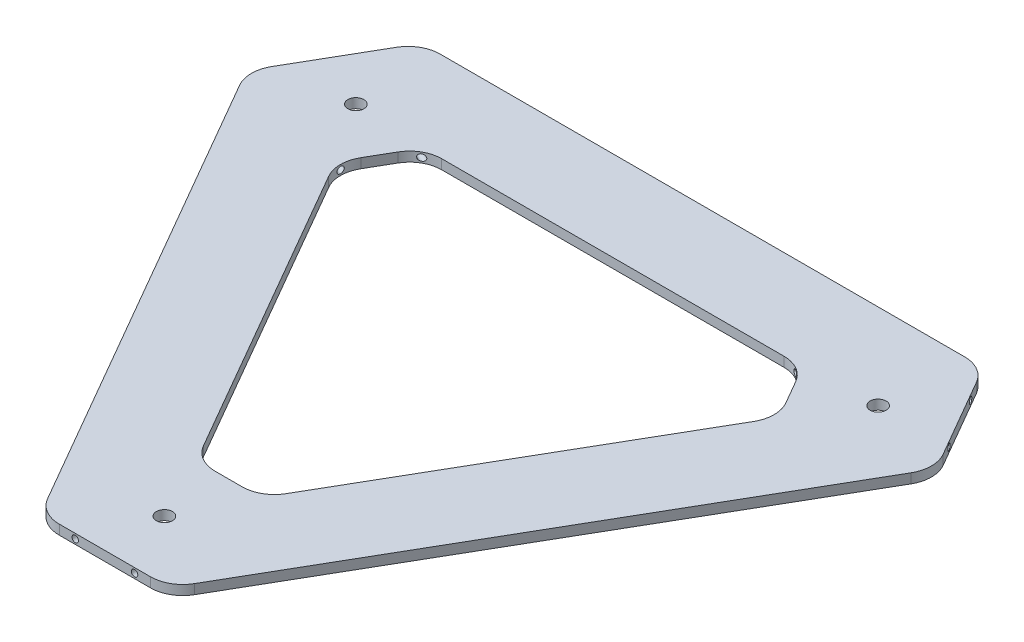
SolidWorks part; units mm, degrees
ref_plane "Front Plane" through (0, 0, 0) normal (0, 0, 1) x (1, 0, 0)
ref_plane "Top Plane" through (0, 0, 0) normal (0, 1, 0) x (1, 0, 0)
ref_plane "Right Plane" through (0, 0, 0) normal (1, 0, 0) x (0, 0, -1)
sketch "Sketch1" plane through (0, 0, 0) normal (0, 1, 0) x (1, 0, 0)
  line L0 (-132.8622, 80.6266) -> (-114.8184, 111.8764)
  line L1 (114.7578, 111.8982) -> (132.8579, 80.6002)
  line L2 (-103.821, 118.2259) -> (103.763, 118.2403)
  line L3 (-18.0944, -118.2403) -> (18.0401, -118.2403)
  line L4 (-132.8638, 67.9283) -> (-29.0942, -111.8881)
  line L5 (132.8618, 67.891) -> (29.038, -111.8915)
  line L6 (-84.0133, 67.0223) -> (-78.6427, 76.3234)
  line L7 (84.1416, 67.0751) -> (78.7703, 76.363)
  line L8 (-84.0158, 54.3257) -> (-16.3805, -62.9162)
  line L9 (-5.3798, -69.27) -> (5.3567, -69.27)
  line L10 (16.3521, -62.9253) -> (84.1432, 54.3618)
  line L11 (67.7734, 82.705) -> (-67.6475, 82.673)
  arc A0 (18.0401, -118.2403) -> (29.038, -111.8915) centre (18.0401, -105.5403) ccw
  arc A1 (-29.0942, -111.8881) -> (-18.0944, -118.2403) centre (-18.0944, -105.5403) ccw
  arc A2 (132.8618, 67.891) -> (132.8579, 80.6002) centre (121.864, 74.2422) ccw
  arc A3 (114.7578, 111.8982) -> (103.763, 118.2403) centre (103.7639, 105.5403) ccw
  arc A4 (-103.821, 118.2259) -> (-114.8184, 111.8764) centre (-103.8201, 105.5259) ccw
  arc A5 (-132.8622, 80.6266) -> (-132.8638, 67.9283) centre (-121.864, 74.2761) ccw
  arc A6 (-16.3805, -62.9162) -> (-5.3798, -69.27) centre (-5.3798, -56.57) ccw
  arc A7 (5.3567, -69.27) -> (16.3521, -62.9253) centre (5.3567, -56.57) ccw
  arc A8 (84.1432, 54.3618) -> (84.1416, 67.0751) centre (73.1477, 60.7171) ccw
  arc A9 (78.7703, 76.363) -> (67.7734, 82.705) centre (67.7764, 70.005) ccw
  arc A10 (-67.6475, 82.673) -> (-78.6427, 76.3234) centre (-67.6445, 69.973) ccw
  arc A11 (-84.0133, 67.0223) -> (-84.0158, 54.3257) centre (-73.015, 60.6719) ccw
  circle A12 centre (-103.3309, 84.381) radius 3.175
  circle A13 centre (-0.0284, -94.7026) radius 3.175
  circle A14 centre (103.3369, 84.3971) radius 3.175
  dimension "D1" = 6.35
  dimension "D2" = 12.7
  dimension "D4" = 5.3567
  dimension "D5" = 16.3521
  dimension "D6" = 18.0401
  dimension "D7" = 29.038
  dimension "D8" = 67.7734
  dimension "D9" = 67.7764
  dimension "D10" = 73.1477
  dimension "D11" = 78.7703
  dimension "D12" = 103.763
  dimension "D13" = 103.3369
  dimension "D14" = 103.7639
  dimension "D15" = 114.7578
  dimension "D16" = 121.864
  dimension "D17" = 5.3798
  dimension "D18" = 16.3805
  dimension "D19" = 18.0944
  dimension "D20" = 0.0284
  dimension "D21" = 29.0942
  dimension "D22" = 67.6445
  dimension "D23" = 73.015
  dimension "D24" = 103.8201
  dimension "D25" = 114.8184
  dimension "D26" = 54.3257
  dimension "D27" = 67.891
  dimension "D31" = 103.3309
  dimension "D45" = 84.381
  dimension "D46" = 84.3971
  dimension "D57" = 94.7026
extrude "Boss-Extrude1" add sketch "Sketch1" along normal blind 3.81
sketch "Sketch2" plane through (0, 0, 0) normal (0, 1, 0) x (1, 0, 0)
  line L0 (-80.979, -21.9799) -> (123.8078, 96.2492) construction
  line L1 (-132.8638, 67.9283) -> (-29.0942, -111.8881) construction
  line L2 (114.7578, 111.8982) -> (132.8579, 80.6002) construction
  line L3 (-0.029, 118.2331) -> (-0.0271, -118.2403) construction
  line L4 (-103.821, 118.2259) -> (103.763, 118.2403) construction
  line L5 (-18.0944, -118.2403) -> (18.0401, -118.2403) construction
  line L6 (80.9499, -22.0002) -> (-123.8403, 96.2515) construction
  line L7 (132.8618, 67.891) -> (29.038, -111.8915) construction
  line L8 (-132.8622, 80.6266) -> (-114.8184, 111.8764) construction
  line L9 (-129.7133, 86.0802) -> (-136.3122, 89.8906) construction
  line L10 (-117.967, 106.4226) -> (-124.5659, 110.233) construction
  line L11 (-117.967, 106.4226) -> (-0.0283, 24.7552) construction
  line L12 (-0.0283, 24.7552) -> (-129.7133, 86.0802) construction
  line L13 (-129.7133, 86.0802) -> (-85.715, 60.6744) construction
  line L14 (129.6671, 86.0594) -> (136.2665, 89.8691) construction
  line L15 (117.9233, 106.4032) -> (124.5226, 110.2128) construction
  line L16 (129.6671, 86.0594) -> (-0.0283, 24.7552) construction
  line L17 (-0.0283, 24.7552) -> (117.9233, 106.4032) construction
  line L18 (-11.7849, -118.2164) -> (-11.7854, -125.8364) construction
  line L19 (11.7052, -118.2178) -> (11.7048, -125.8378) construction
  line L20 (-11.7849, -118.2164) -> (-0.0283, 24.7552) construction
  line L21 (-0.0283, 24.7552) -> (11.7052, -118.2178) construction
  line L22 (-108.0075, 24.7552) -> (107.951, 24.7552) construction
  line L23 (29.038, -111.8915) -> (132.8618, 67.891) construction
  arc A0 (-84.0133, 67.0223) -> (-84.0158, 54.3257) centre (-73.015, 60.6719) ccw construction
  point P18 (-0.0283, 24.7552)
  point P27 (-0.0283, 24.7552)
  dimension "D1" = 7.62
  dimension "D2" = 3
sketch "Sketch3" plane through (134.4902, 0, -77.7777) normal (0.8657, 0, -0.5006) x (-0.5006, 0, -0.8657)
  line L0 (9.5837, 1.905) -> (33.0739, 1.905) construction
  line L1 (9.5837, 1.905) -> (9.5837, 0) construction
  line L2 (9.5837, 0) -> (9.5778, 0) construction
  line L3 (33.0739, 1.905) -> (33.0739, 0) construction
  line L5 (3.2605, 0) -> (39.4154, 0) construction
  line L6 (21.3379, 3.81) -> (21.3379, 0) construction
  line L7 (3.2605, 3.81) -> (39.4154, 3.81) construction
  circle A0 centre (9.5837, 1.905) radius 1.27
  circle A1 centre (33.0739, 1.905) radius 1.27
  point P4 (21.3379, 1.905)
  dimension "D1" = 2.54
extrude "Cut-Extrude1" cut sketch "Sketch3" against normal up to next
sketch "Sketch5" plane through (0, 0, 118.2403) normal (0, 0, 1) x (1, 0, 0)
  line L0 (-11.7849, 1.905) -> (11.7052, 1.905) construction
  line L1 (-11.7849, 1.905) -> (-11.7849, 0) construction
  line L2 (11.7052, 1.905) -> (11.7052, 0) construction
  line L3 (-0.0271, 3.81) -> (-0.0271, 0) construction
  line L4 (11.7052, 0) -> (11.7048, 0) construction
  line L5 (-0.029, 0) -> (-0.0271, 0) construction
  line L6 (-18.0944, 0) -> (18.0401, 0) construction
  line L7 (-18.0944, 3.81) -> (18.0401, 3.81) construction
  circle A0 centre (-11.7849, 1.905) radius 1.27
  circle A1 centre (11.7052, 1.905) radius 1.27
  point P4 (-0.0271, 1.905)
  point P9 (0, 0)
  point P11 (0, 0)
  point P14 (0, 0)
  point P17 (10.4465, 0)
  point P21 (-11.7849, 2.1883)
  point P22 (0, 0)
  point P25 (2.7242, 3.81)
  point P26 (0, 0)
  point P27 (0, 0)
  dimension "D1" = 2.54
extrude "Cut-Extrude2" cut sketch "Sketch5" against normal up to next
sketch "Sketch6" plane through (-134.5558, 0, -77.6936) normal (-0.866, 0, -0.5) x (-0.5, 0, 0.866)
  line L0 (-33.1744, 1.905) -> (-9.6843, 1.905) construction
  line L1 (-33.1744, 1.905) -> (-33.1744, 0) construction
  line L2 (-9.6843, 1.905) -> (-9.6843, 0) construction
  line L3 (-21.4294, 3.81) -> (-21.4294, 0) construction
  line L4 (-39.4719, 3.81) -> (-3.3868, 3.81) construction
  line L5 (-39.4719, 0) -> (-3.3868, 0) construction
  circle A0 centre (-33.1744, 1.905) radius 1.27
  circle A1 centre (-9.6843, 1.905) radius 1.27
  point P4 (-21.4294, 1.905)
  point P11 (0, 0)
  point P14 (-35.2064, 0)
  dimension "D1" = 2.54
extrude "Cut-Extrude3" cut sketch "Sketch6" against normal up to next
